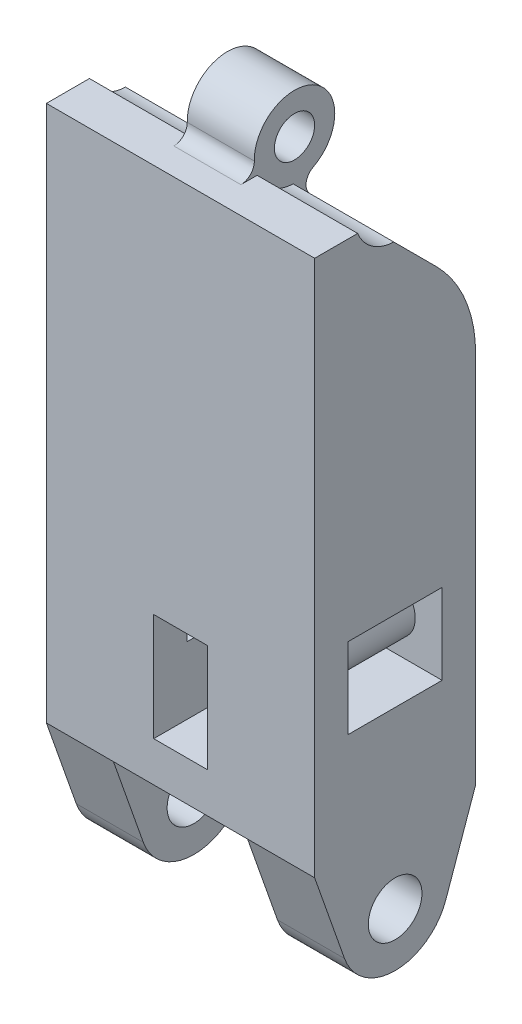
SolidWorks part; units mm, degrees
ref_plane "Front Plane" through (0, 0, 0) normal (0, 0, 1) x (1, 0, 0)
ref_plane "Top Plane" through (0, 0, 0) normal (0, 1, 0) x (1, 0, 0)
ref_plane "Right Plane" through (0, 0, 0) normal (1, 0, 0) x (0, 0, -1)
sketch "Sketch1" plane through (0, 0, 0) normal (0, 0, 1) x (1, 0, 0)
  line L0 (-10, 0) -> (10, 0)
  line L1 (10, 0) -> (10, -40)
  line L2 (-10, 0) -> (-10, -40)
  line L3 (-10, -40) -> (10, -40)
  point P4 (0, 0)
extrude "Boss-Extrude1" add sketch "Sketch1" along normal blind 12
sketch "Sketch2" plane through (0, 0, 0) normal (1, 0, 0) x (0, 0, -1)
  line L0 (-12, 0) -> (-8, 0)
  line L1 (-12, 0) -> (0, 0) construction
  line L2 (0, -40) -> (0, 0) construction
  line L3 (-8, 0) -> (0, 0)
  line L6 (0, 0) -> (0, -8)
  line L7 (-8, 0) -> (0, -8)
extrude "Cut-Extrude1" cut sketch "Sketch2" against normal through all both and the other way through all contours L3 L6 L7
sketch "Sketch3" plane through (0, 0, 0) normal (1, 0, 0) x (0, 0, -1)
  line L0 (-12, 0) -> (0, 0)
  line L1 (-12, -40) -> (-12, 0) construction
  line L2 (-12, 0) -> (-8, 0) construction
  line L3 (-6, 0) -> (-6, 1.1)
  circle A0 centre (-6, 1.1) radius 1.5
  circle A1 centre (-6, 1.1) radius 3
extrude "Cut-Extrude2" cut sketch "Sketch3" against normal through all both and the other way through all contours L0 A1 A0 | L0 A1 A0
sketch "Sketch4" plane through (0, 0, 0) normal (1, 0, 0) x (0, 0, -1)
  circle A0 centre (-6, 1.1) radius 1.5
  circle A1 centre (-6, 1.1) radius 3
extrude "Boss-Extrude2" add sketch "Sketch4" along normal mid plane 5
fillet "Fillet1" radius 1 2 edges at (0, 0, 8.7911) (0, -1.8983, 6.1017)
sketch "Sketch5" plane through (10, 0, 0) normal (1, 0, 0) x (0, 0, -1)
  line L0 (-2.2268, -46.3278) -> (0, -40)
  line L1 (-12, -40) -> (0, -40) construction
  line L2 (-12, -40) -> (-9.7732, -46.3278)
  line L3 (-12, -40) -> (0, -40)
  arc A0 (-9.7732, -46.3278) -> (-2.2268, -46.3278) centre (-6, -45) ccw
  circle A1 centre (-6, -45) radius 2
  point P8 (-6, -40)
  dimension "D1" = 5
  dimension "D2" = 8
extrude "Boss-Extrude3" add sketch "Sketch5" against normal blind 5 contours L3 L0 A0 L2 | A1
sketch "Sketch7" plane through (-10, 0, 0) normal (-1, 0, 0) x (0, 0, 1)
  line L0 (12, -40) -> (0, -40)
  line L1 (0, -40) -> (2.2268, -46.3278)
  line L2 (12, -40) -> (9.7732, -46.3278)
  circle A0 centre (6, -45) radius 2
  arc A1 (2.2268, -46.3278) -> (9.7732, -46.3278) centre (6, -45) ccw
extrude "Boss-Extrude4" add sketch "Sketch7" against normal blind 5
fillet "Fillet2" radius 10 1 edges at (0, -8, 0)
sketch "Sketch8" plane through (-10, 0, 0) normal (-1, 0, 0) x (0, 0, 1)
  line L6 (2.5, -26) -> (9.5, -26)
  line L7 (2.5, -26) -> (2.5, -32)
  line L8 (2.5, -32) -> (9.5, -32)
  line L9 (9.5, -26) -> (9.5, -32)
  point P5 (6, -30)
extrude "Cut-Extrude3" cut sketch "Sketch8" against normal blind 8
sketch "Sketch10" plane through (0, 0, 9.5) normal (0, 0, -1) x (-1, 0, 0)
  circle A0 centre (6, -29) radius 2
extrude "Boss-Extrude5" add sketch "Sketch10" along normal up to surface (7 mm away) up to face at (-6, -29, 2.5)
sketch "Sketch11" plane through (10, 0, 0) normal (1, 0, 0) x (0, 0, -1)
  line L0 (-9.5, -26) -> (-9.5, -32)
  line L1 (-9.5, -32) -> (-2.5, -32)
  line L2 (-9.5, -26) -> (-2.5, -26)
  line L3 (-2.5, -32) -> (-2.5, -26)
extrude "Cut-Extrude4" cut sketch "Sketch11" against normal blind 8
sketch "Sketch12" plane through (0, 0, 9.5) normal (0, 0, -1) x (-1, 0, 0)
  circle A0 centre (-6, -29) radius 2
extrude "Boss-Extrude6" add sketch "Sketch12" along normal blind 8
sketch "Sketch13" plane through (0, 0, 0) normal (0, 0, -1) x (-1, 0, 0)
  line L5 (-2, -37.0178) -> (2, -37.0178)
  line L6 (-2, -37.0178) -> (-2, -29.0178)
  line L7 (-2, -29.0178) -> (2, -29.0178)
  line L8 (2, -37.0178) -> (2, -29.0178)
  line L9 (-2, -37.0178) -> (2, -29.0178) construction
  line L10 (-2, -29.0178) -> (2, -37.0178) construction
  line L13 (-2, -23.0888) -> (2, -23.0888)
  line L14 (-2, -23.0888) -> (-2, -15.0888)
  line L15 (-2, -15.0888) -> (2, -15.0888)
  line L16 (2, -23.0888) -> (2, -15.0888)
  line L17 (-2, -23.0888) -> (2, -15.0888) construction
  line L18 (-2, -15.0888) -> (2, -23.0888) construction
  point P9 (0, -33.0178)
  point P14 (0, -19.0888)
extrude "Cut-Extrude5" cut sketch "Sketch13" against normal blind 6
sketch "Sketch16" plane through (0, -29.0178, 0) normal (0, -1, 0) x (1, 0, 0)
  line L0 (2, 6) -> (2, 3)
  line L2 (2, 3) -> (-2, 3)
  line L4 (2, 6) -> (-2, 6)
  line L5 (-2, 3) -> (-2, 6)
extrude "Cut-Extrude6" cut sketch "Sketch16" against normal blind 6 contours L0 L2 L5 L4
sketch "Sketch17" plane through (0, 0, 0) normal (0, 0, -1) x (-1, 0, 0)
  line L0 (-2, -26) -> (-2, -32) construction
  line L1 (-2, -29) -> (2, -29)
  line L2 (-2, -29) -> (-2, -37.0178)
  line L3 (-2, -37.0178) -> (2, -37.0178)
  line L4 (2, -29) -> (2, -37.0178)
extrude "Cut-Extrude7" cut sketch "Sketch17" against normal through all
